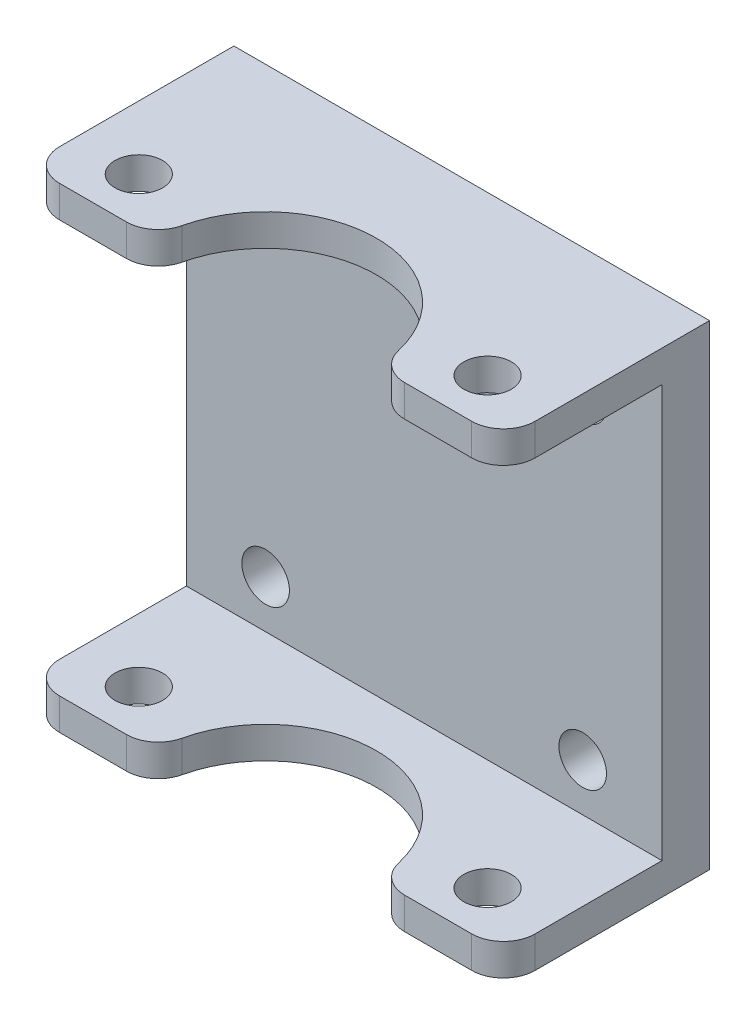
SolidWorks part; units mm, degrees
ref_plane "前视基准面" through (0, 0, 0) normal (0, 0, 1) x (1, 0, 0)
ref_plane "上视基准面" through (0, 0, 0) normal (0, 1, 0) x (1, 0, 0)
ref_plane "右视基准面" through (0, 0, 0) normal (1, 0, 0) x (0, 0, -1)
sketch "草图1" plane through (0, 0, 0) normal (0, 0, 1) x (1, 0, 0)
  line L1 (-15, 15) -> (15, 15)
  line L2 (-15, 15) -> (-15, -15)
  line L3 (-15, -15) -> (15, -15)
  line L4 (15, 15) -> (15, -15)
  line L5 (-15, 15) -> (15, -15) construction
  line L6 (-15, -15) -> (15, 15) construction
  circle A0 centre (-10, 10) radius 1.5
  circle A1 centre (10, 10) radius 1.5
  circle A2 centre (-10, -10) radius 1.5
  circle A3 centre (10, -10) radius 1.5
  point P0 (0, 0)
  dimension "D3" = 3
  dimension "D4" = 5
  dimension "D5" = 5
  dimension "D6" = 3
  dimension "D7" = 5
  dimension "D8" = 5
  dimension "D9" = 3
  dimension "D10" = 5
  dimension "D11" = 5
  dimension "D12" = 3
  dimension "D13" = 5
  dimension "D14" = 5
  dimension "D1" = 30
  dimension "D2" = 30
extrude "凸台-拉伸1" add sketch "草图1" along normal blind 3
sketch "草图2" plane through (0, 0, 3) normal (0, 0, 1) x (1, 0, 0)
  line L0 (0, 15) -> (0, -15) construction
  line L1 (15, 15) -> (-15, 15) construction
  line L2 (-15, -15) -> (15, -15) construction
  line L3 (15, -15) -> (15, 15) construction
  line L4 (-15, 15) -> (15, 15)
  line L5 (-15, 15) -> (-15, 13)
  line L6 (-15, 13) -> (15, 13)
  line L7 (15, 15) -> (15, 13)
  line L9 (-15, -15) -> (15, -15)
  line L10 (-15, -15) -> (-15, -13)
  line L11 (-15, -13) -> (15, -13)
  line L12 (15, -15) -> (15, -13)
  dimension "D1" = 2
  dimension "D2" = 2
extrude "凸台-拉伸2" add sketch "草图2" along normal blind 18
sketch "草图3" plane through (0, 13, 0) normal (0, -1, 0) x (1, 0, 0)
  line L0 (0, 3) -> (0, 21) construction
  line L1 (-15, 0) -> (15, 0) construction
  line L7 (-15, 3) -> (15, 3) construction
  line L8 (-15, 21) -> (15, 21) construction
  line L9 (-15, 12) -> (15, 12) construction
  line L10 (-15, 21) -> (-15, 3) construction
  line L11 (15, 21) -> (15, 3) construction
  circle A4 centre (-11, 10) radius 1.5
  circle A5 centre (11, 10) radius 1.5
  dimension "D2" = 3
  dimension "D3" = 11
  dimension "D4" = 10
extrude "切除-拉伸1" cut sketch "草图3" against normal through all both and the other way through all
sketch "草图4" plane through (0, -15, 0) normal (0, -1, 0) x (1, 0, 0)
  line L0 (0, 21) -> (0, 0) construction
  line L1 (-15, 21) -> (15, 21) construction
  line L2 (15, 10.5) -> (-15, 10.5) construction
  line L3 (15, 21) -> (15, 0) construction
  line L4 (-15, 21) -> (-15, 0) construction
  line L5 (-15, 3) -> (15, 3) construction
  line L6 (-7, 13) -> (-16.4911, 13)
  line L7 (-16.4911, 13) -> (-16.4911, 22.2347)
  line L8 (-16.4911, 22.2347) -> (16.3659, 22.2347)
  line L9 (16.3659, 22.2347) -> (16.3659, 13)
  line L10 (16.3659, 13) -> (7, 13)
  arc A3 (-7, 13) -> (7, 13) centre (0, 13) ccw
  dimension "D1" = 14
  dimension "D2" = 10
extrude "切除-拉伸2" cut sketch "草图4" against normal through all
fillet "圆角1" radius 2 8 edges at (7, -14, 13) (15, -14, 13) (15, 14, 13) (7, 14, 13) (-7, 14, 13) (-15, 14, 13) (-7, -14, 13) (-15, -14, 13)
